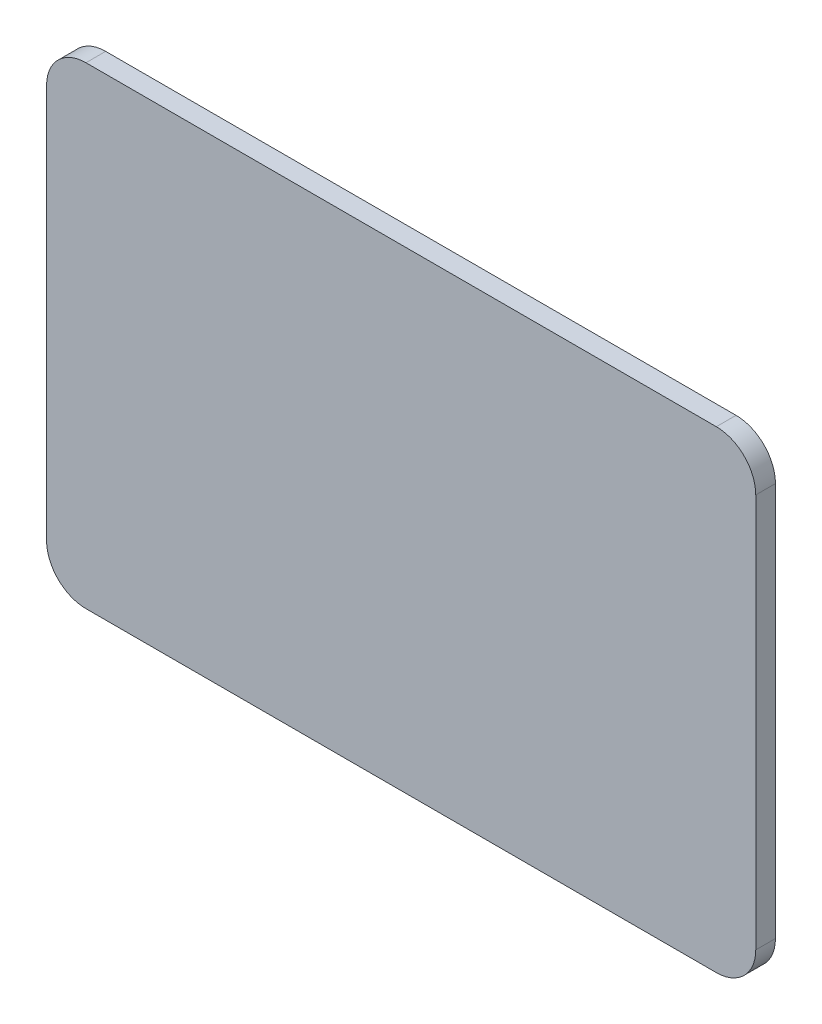
SolidWorks part; units mm, degrees
material "PC High Viscosity"
ref_plane "X-Y Datum" through (0, 0, 0) normal (0, 0, 1) x (1, 0, 0)
ref_plane "X-Z Datum" through (0, 0, 0) normal (0, 1, 0) x (1, 0, 0)
ref_plane "Y-Z Datum" through (0, 0, 0) normal (1, 0, 0) x (0, 0, -1)
sketch "Sketch1" plane through (0, 0, 0) normal (0, 0, 1) x (1, 0, 0)
  line L1 (-57.15, 38.1) -> (57.15, 38.1)
  line L2 (-57.15, 38.1) -> (-57.15, -38.1)
  line L3 (-57.15, -38.1) -> (57.15, -38.1)
  line L4 (57.15, 38.1) -> (57.15, -38.1)
  line L5 (-57.15, 38.1) -> (57.15, -38.1) construction
  line L6 (-57.15, -38.1) -> (57.15, 38.1) construction
  point P0 (0, 0)
  dimension "D1" = 114.3
  dimension "D2" = 76.2
extrude "Boss-Extrude1" add sketch "Sketch1" along normal blind 3.175
fillet "Fillet1" radius 6.35 4 edges at (57.15, -38.1, 1.5875) (57.15, 38.1, 1.5875) (-57.15, 38.1, 1.5875) (-57.15, -38.1, 1.5875)
